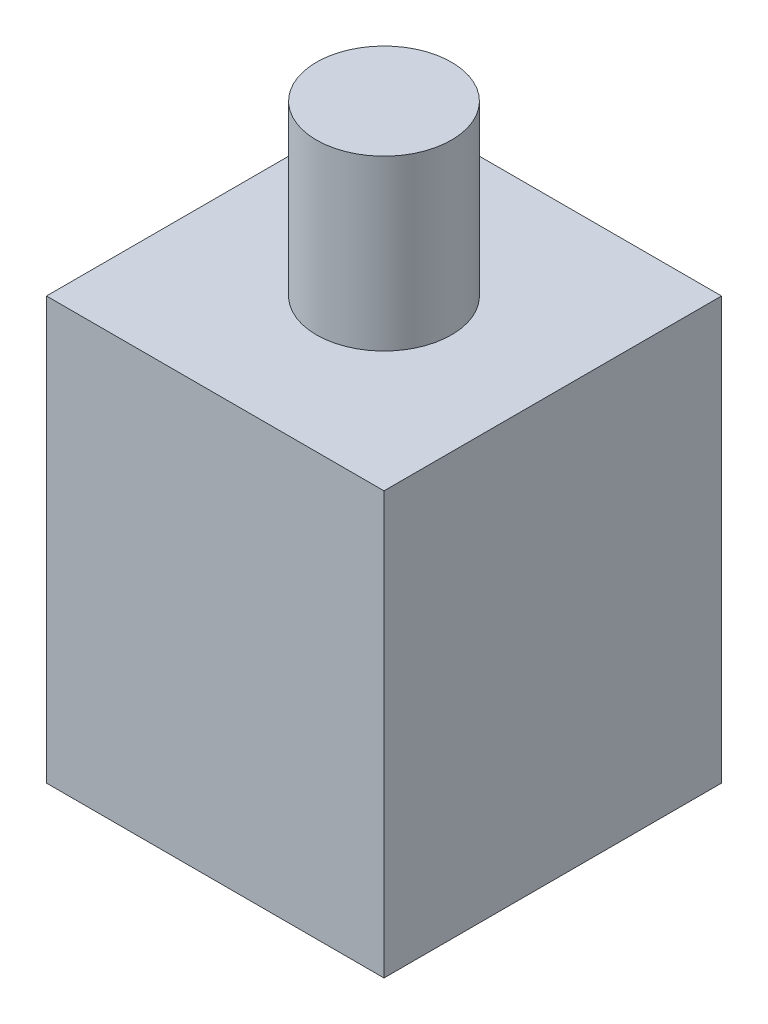
SolidWorks part; units mm, degrees
ref_plane "前视基准面" through (0, 0, 0) normal (0, 0, 1) x (1, 0, 0)
ref_plane "上视基准面" through (0, 0, 0) normal (0, 1, 0) x (1, 0, 0)
ref_plane "右视基准面" through (0, 0, 0) normal (1, 0, 0) x (0, 0, -1)
other "Configuration Table"
sketch "草图1" plane through (0, 0, 0) normal (0, 1, 0) x (1, 0, 0)
  line L1 (-20, 20) -> (20, 20)
  line L2 (-20, 20) -> (-20, -20)
  line L3 (-20, -20) -> (20, -20)
  line L4 (20, 20) -> (20, -20)
  line L5 (-20, 20) -> (20, -20) construction
  line L6 (-20, -20) -> (20, 20) construction
  point P0 (0, 0)
  dimension "D1" = 40
  dimension "D2" = 40
extrude "凸台-拉伸1" add sketch "草图1" along normal blind 50
sketch "草图2" plane through (0, 50, 0) normal (0, 1, 0) x (1, 0, 0)
  circle A0 centre (0, 0) radius 8
  dimension "D1" = 16
extrude "凸台-拉伸2" add sketch "草图2" along normal blind 20 separate body
